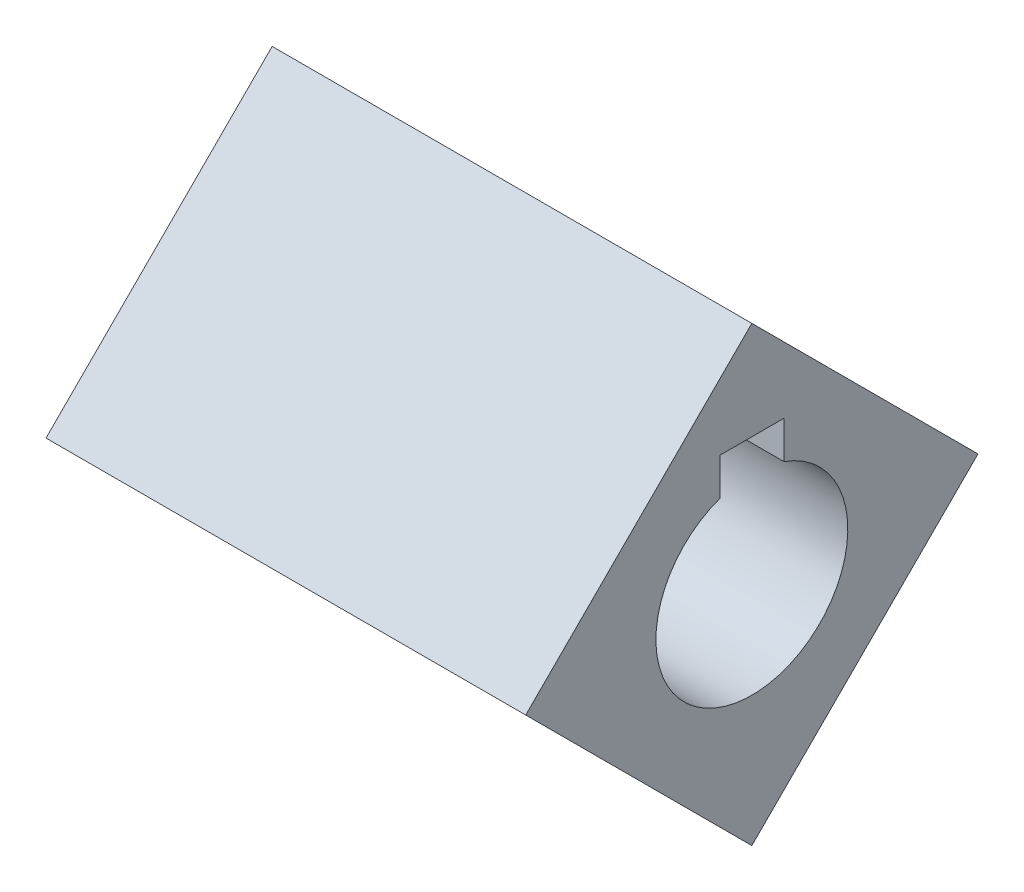
SolidWorks part; units mm, degrees
material "Plain Carbon Steel"
ref_plane "Front Plane" through (0, 0, 0) normal (0, 0, 1) x (1, 0, 0)
ref_plane "Top Plane" through (0, 0, 0) normal (0, 1, 0) x (1, 0, 0)
ref_plane "Right Plane" through (0, 0, 0) normal (1, 0, 0) x (0, 0, -1)
sketch "Sketch1" plane through (0, 0, 0) normal (0, 0, 1) x (1, 0, 0)
  line L0 (0, 0) -> (0, 17.5)
  line L1 (0, 17.5) -> (30, 17.5)
  line L2 (30, 17.5) -> (30, 0)
  line L3 (30, 0) -> (0, 0)
  line L4 (0, 0) -> (-29.537, 0) construction
  dimension "D1" = 35
  dimension "D2" = 30
revolve "Revolve1" add sketch "Sketch1" angle 360 about L4
sketch "Sketch5" plane through (0, 0, 0) normal (-1, 0, 0) x (0, 0, 1)
  circle A0 centre (0, 0) radius 6
  dimension "D1" = 12
extrude "Cut-Extrude3" cut sketch "Sketch5" against normal through all
sketch "Sketch6" plane through (0, 0, 0) normal (-1, 0, 0) x (0, 0, 1)
  line L0 (-2, 8) -> (-2, 4)
  line L1 (-2, 8) -> (2, 8)
  line L2 (-2, 4) -> (2, 4)
  line L3 (2, 8) -> (2, 4)
  line L4 (-2, 8) -> (2, 4) construction
  line L5 (-2, 4) -> (2, 8) construction
  line L6 (0, 0) -> (0, 6) construction
  circle A0 centre (0, 0) radius 6 construction
  point P1 (0, 6)
  dimension "D1" = 4
extrude "Cut-Extrude5" cut sketch "Sketch6" against normal through all
sketch "Sketch7" plane through (30, 0, 0) normal (1, 0, 0) x (0, 0, -1)
  line L0 (-14.1421, 0) -> (0, -14.1421)
  line L1 (-14.1421, 0) -> (0, 14.1421)
  line L2 (0, -14.1421) -> (14.1421, 0)
  line L3 (0, 14.1421) -> (14.1421, 0)
  line L4 (-14.1421, 0) -> (14.1421, 0) construction
  line L5 (0, -14.1421) -> (0, 14.1421) construction
  point P1 (0, 0)
  dimension "D1" = 20
extrude "Cut-Extrude6" cut sketch "Sketch7" against normal through all flip side to cut
